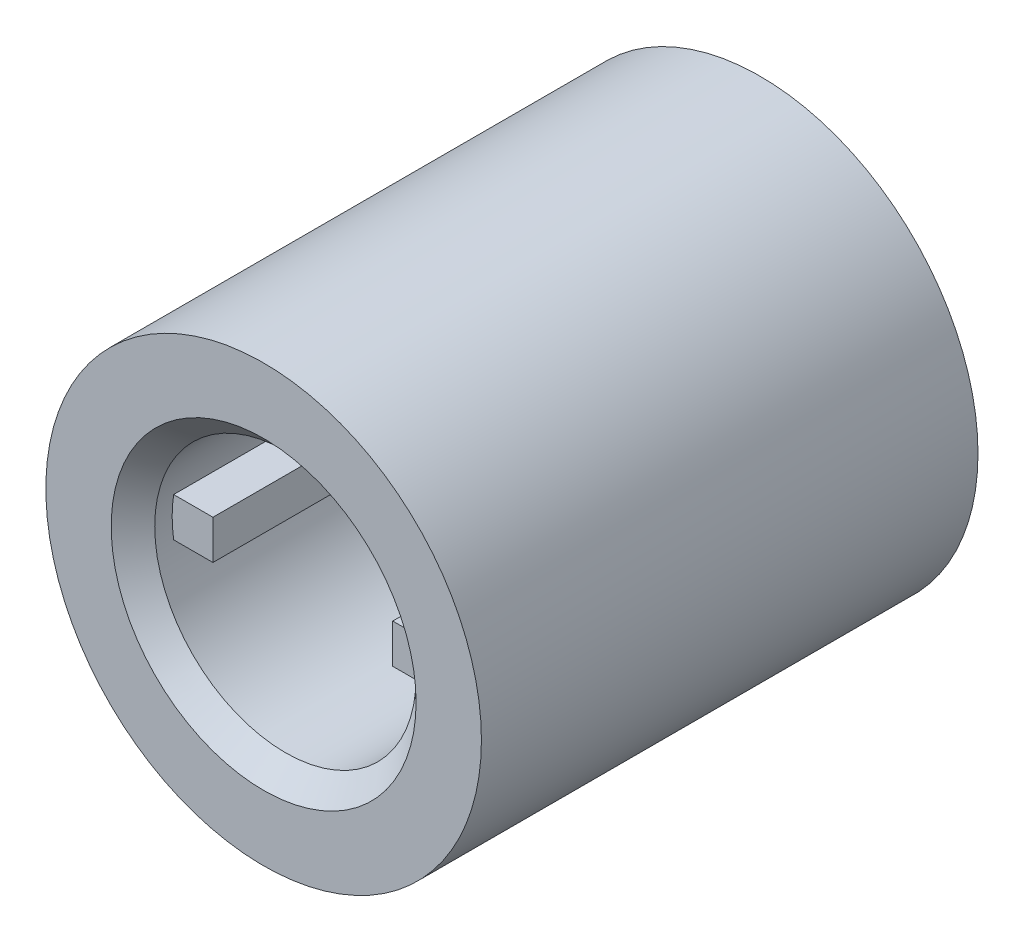
SolidWorks part; units mm, degrees
ref_plane "前视基准面" through (0, 0, 0) normal (0, 0, 1) x (1, 0, 0)
ref_plane "上视基准面" through (0, 0, 0) normal (0, 1, 0) x (1, 0, 0)
ref_plane "右视基准面" through (0, 0, 0) normal (1, 0, 0) x (0, 0, -1)
other "Configuration Table"
sketch "草图1" plane through (0, 0, 0) normal (0, 0, 1) x (1, 0, 0)
  circle A0 centre (0, 0) radius 3
  dimension "D1" = 6
extrude "拉伸-薄壁1" add sketch "草图1" along normal blind 3.9 and the other way blind 7.5 thin
chamfer "倒角1" distance 0.5 angle 45 2 edges at (3, 0, 3.9) (3, 0, -7.5)
sketch "草图2" plane through (0, 0, 0) normal (0, 0, 1) x (1, 0, 0)
  line L0 (0, 1.3883) -> (0, -1.5632) construction
  line L1 (-3.3059, 0.45) -> (-2.0637, 0.45)
  line L2 (-3.3059, 0.45) -> (-3.3059, -0.45)
  line L3 (-3.3059, -0.45) -> (-2.0637, -0.45)
  line L4 (-2.0637, 0.45) -> (-2.0637, -0.45)
  line L5 (-3.3059, 0.45) -> (-2.0637, -0.45) construction
  line L6 (-3.3059, -0.45) -> (-2.0637, 0.45) construction
  line L7 (3.3059, -0.45) -> (2.0637, -0.45)
  line L8 (2.0637, 0.45) -> (2.0637, -0.45)
  line L9 (3.3059, 0.45) -> (2.0637, 0.45)
  line L10 (3.3059, 0.45) -> (3.3059, -0.45)
  line L11 (-2.6848, 0) -> (0, 0) construction
  point P0 (-2.6848, 0)
  dimension "D1" = 0.9
extrude "凸台-拉伸1" add sketch "草图2" along normal blind 3
